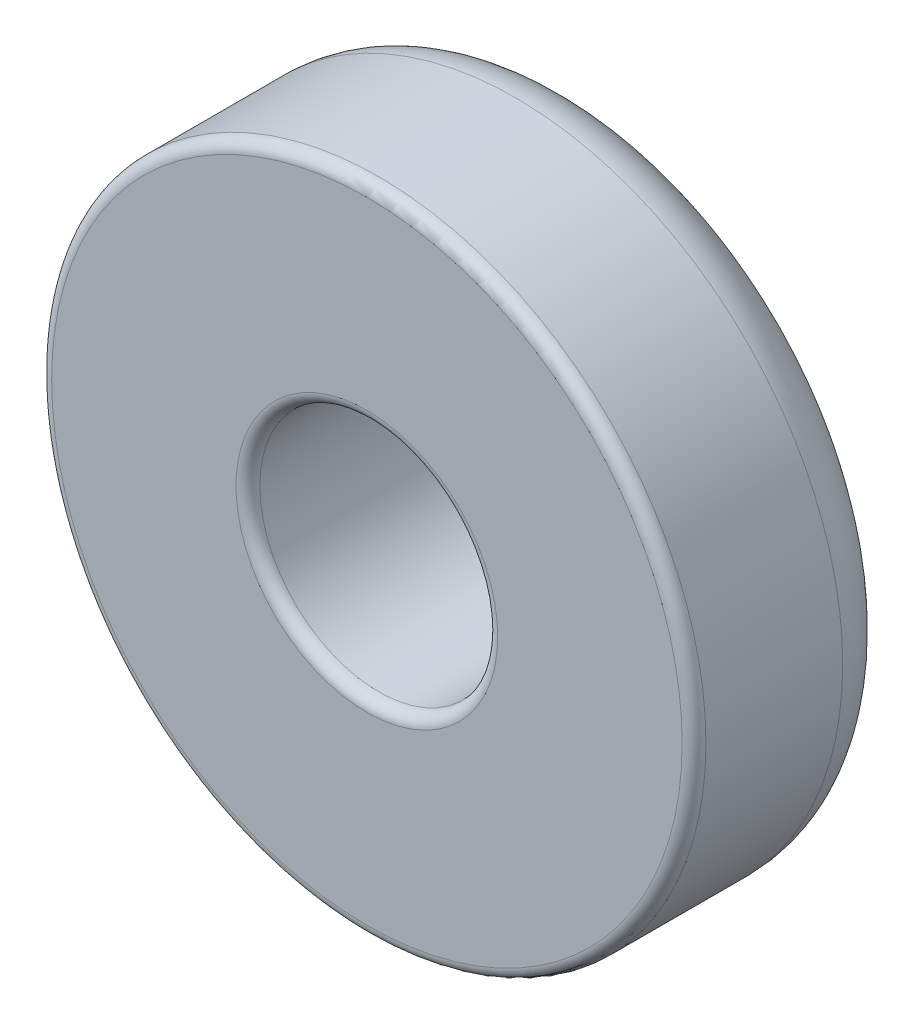
SolidWorks part; units mm, degrees
ref_plane "Front Plane" through (0, 0, 0) normal (0, 0, 1) x (1, 0, 0)
ref_plane "Top Plane" through (0, 0, 0) normal (0, 1, 0) x (1, 0, 0)
ref_plane "Right Plane" through (0, 0, 0) normal (1, 0, 0) x (0, 0, -1)
sketch "Sketch1" plane through (0, 0, 0) normal (0, 0, 1) x (1, 0, 0)
  circle A0 centre (0, 0) radius 1
  dimension "D1" = 2
extrude "Extrude-Thin1" add sketch "Sketch1" along normal blind 1.75 thin
fillet "Fillet1" radius 0.5 1 edges at (2.75, 0, 0)
fillet "Fillet2" radius 0.1 3 edges at (1, 0, 0) (2.75, 0, 1.75) (1, 0, 1.75)
